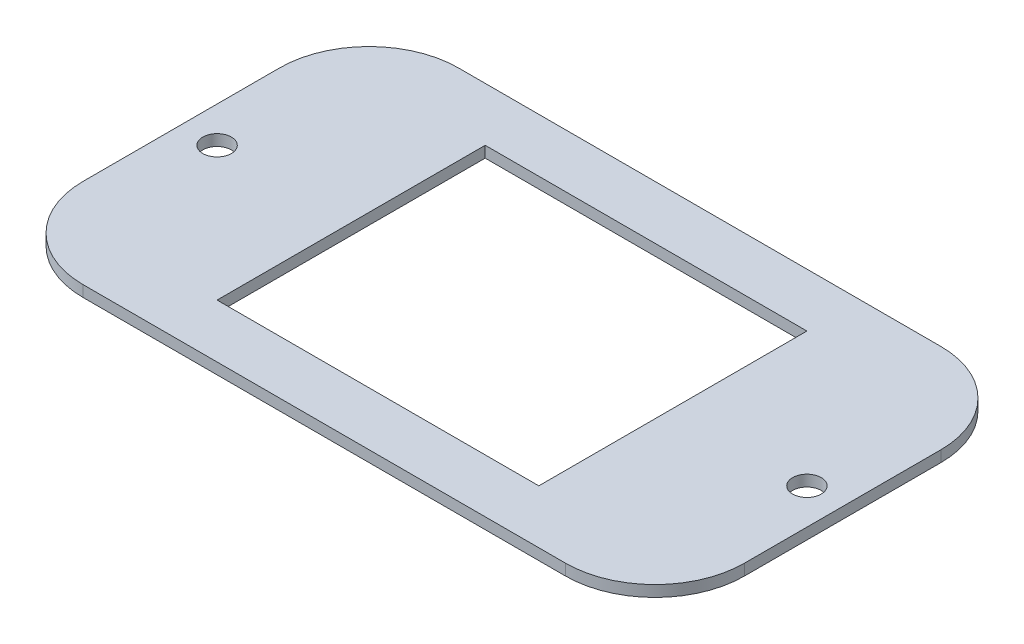
SolidWorks part; units mm, degrees
ref_plane "Front Plane" through (0, 0, 0) normal (0, 0, 1) x (1, 0, 0)
ref_plane "Top Plane" through (0, 0, 0) normal (0, 1, 0) x (1, 0, 0)
ref_plane "Right Plane" through (0, 0, 0) normal (1, 0, 0) x (0, 0, -1)
sketch "Sketch1" plane through (0, 0, 0) normal (0, 1, 0) x (1, 0, 0)
  line L0 (-18, 0) -> (-33, 0) construction
  line L1 (-37, -21) -> (37, -21)
  line L2 (-37, -21) -> (-37, 21)
  line L3 (-37, 21) -> (37, 21)
  line L4 (37, -21) -> (37, 21)
  line L5 (-37, -21) -> (37, 21) construction
  line L6 (-37, 21) -> (37, -21) construction
  line L7 (0, 0) -> (0, 10.7319) construction
  line L9 (18, -15) -> (-18, -15)
  line L10 (18, -15) -> (18, 15)
  line L11 (18, 15) -> (-18, 15)
  line L12 (-18, -15) -> (-18, 15)
  line L13 (18, -15) -> (-18, 15) construction
  line L14 (18, 15) -> (-18, -15) construction
  circle A0 centre (-33, 0) radius 1.6
  circle A1 centre (33, 0) radius 1.6
  point P0 (0, 0)
  dimension "D2" = 30
  dimension "D4" = 4
  dimension "D1" = 15
  dimension "D3" = 36
  dimension "D5" = 6
extrude "Boss-Extrude1" add sketch "Sketch1" along normal blind 1.25
fillet "Fillet1" radius 10 4 edges at (37, 0.625, -21) (37, 0.625, 21) (-37, 0.625, -21) (-37, 0.625, 21)
